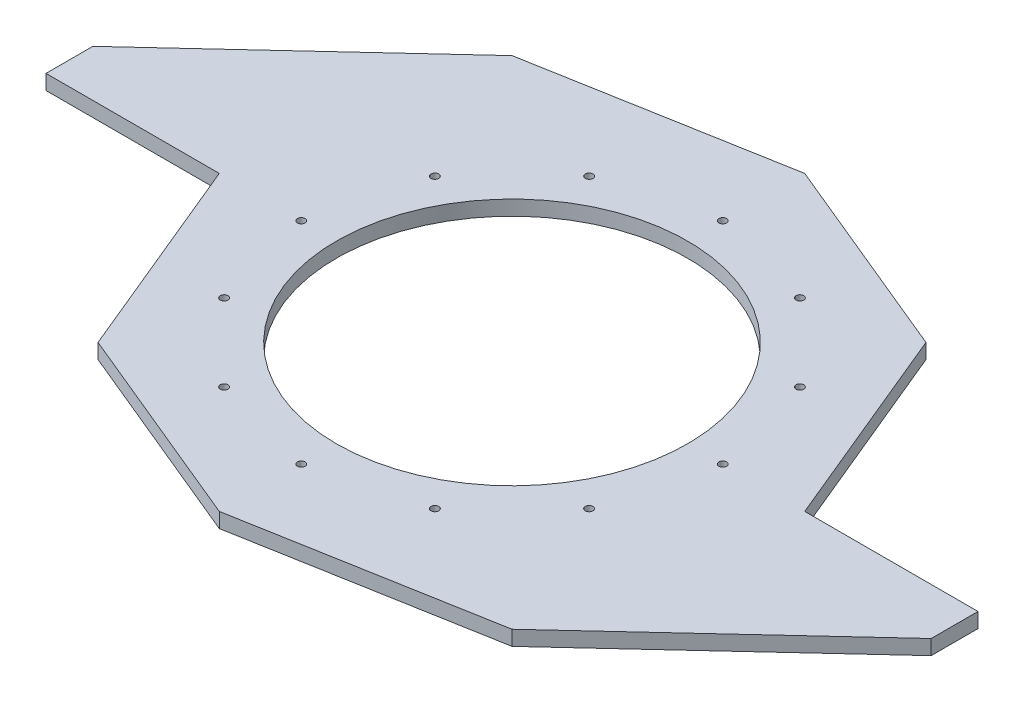
SolidWorks part; units mm, degrees
material "Delrin 2700 NC010, Low Viscosity Acetal Copolymer (SS)"
ref_plane "Front Plane" through (0, 0, 0) normal (0, 0, 1) x (1, 0, 0)
ref_plane "Top Plane" through (0, 0, 0) normal (0, 1, 0) x (1, 0, 0)
ref_plane "Right Plane" through (0, 0, 0) normal (1, 0, 0) x (0, 0, -1)
sketch "Sketch1" plane through (0, 0, 0) normal (0, 1, 0) x (1, 0, 0)
  line L0 (0, 0) -> (0, 249.7021) construction
  line L1 (0, 0) -> (-269.6724, 0) construction
  line L2 (0, 0) -> (0, -199.1875) construction
  line L3 (0, 0) -> (255.8951, 0) construction
  line L4 (0, 0) -> (131.4551, 131.4551) construction
  line L5 (0, 0) -> (-180.2101, 180.2101) construction
  line L6 (0, 0) -> (-129.3295, -129.3295) construction
  line L7 (0, 0) -> (150.7052, -150.7052) construction
  line L8 (125, 0) -> (88.3883, 88.3883)
  line L9 (88.3883, 88.3883) -> (0, 125)
  line L10 (0, 125) -> (-106.066, 106.066)
  line L11 (-106.066, 106.066) -> (-198.9975, 20)
  line L12 (-198.9975, 20) -> (-198.9975, 0)
  line L13 (-125, 0) -> (-88.3883, -88.3883)
  line L14 (-88.3883, -88.3883) -> (0, -125)
  line L15 (0, -125) -> (106.066, -106.066)
  line L16 (106.066, -106.066) -> (198.9975, -20)
  line L17 (198.9975, -20) -> (198.9975, 0)
  line L18 (-198.9975, 0) -> (-125, 0)
  line L19 (198.9975, 0) -> (125, 0)
  circle A0 centre (0, 0) radius 75
  dimension "D1" = 45
  dimension "D2" = 150
  dimension "D3" = 45
  dimension "D4" = 125
  dimension "D5" = 125
  dimension "D6" = 125
  dimension "D7" = 150
  dimension "D8" = 200
  dimension "D9" = 125
  dimension "D10" = 125
  dimension "D11" = 125
  dimension "D12" = 150
  dimension "D13" = 200
  dimension "D14" = 20
  dimension "D15" = 20
extrude "Boss-Extrude1" add sketch "Sketch1" along normal blind 6.35
hole_wizard "CBORE for M3 SHCS1" positions "Sketch2" profile "Sketch3" counterbore size "M3" standard "ANSI Metric" end condition through all
sketch "Sketch2" plane through (0, 0, 0) normal (0, 1, 0) x (1, 0, 0)
  line L0 (0, 0) -> (90, 0) construction
  point P0 (90, 0)
  point P15 (77.9423, -45)
  point P16 (45, -77.9423)
  point P17 (0, -90)
  point P18 (-45, -77.9423)
  point P19 (-77.9423, -45)
  point P20 (-90, 0)
  point P21 (-77.9423, 45)
  point P22 (-45, 77.9423)
  point P23 (0, 90)
  point P24 (45, 77.9423)
  point P25 (77.9423, 45)
  point P38 (0, 0)
  dimension "D1" = 90
  dimension "D2" = 12
sketch "Sketch3" plane through (90, 0, 0) normal (1, 0, 0) x (0, 0, -1)
  line L0 (0, 0) -> (0, 6.35)
  line L1 (0, 6.35) -> (1.65, 6.35)
  line L3 (1.65, 6.35) -> (1.65, 3)
  line L4 (1.65, 3) -> (3, 3)
  line L5 (3, 3) -> (3, 0)
  line L7 (3, 0) -> (0, 0)
  line L11 (0, -6.35) -> (0, 107.95) construction
  dimension "Thru Hole Dia." = 3.3
  dimension "Thru Hole Depth" = 6.35
  dimension "C'Bore Dia." = 6
  dimension "C'Bore Depth" = 3
